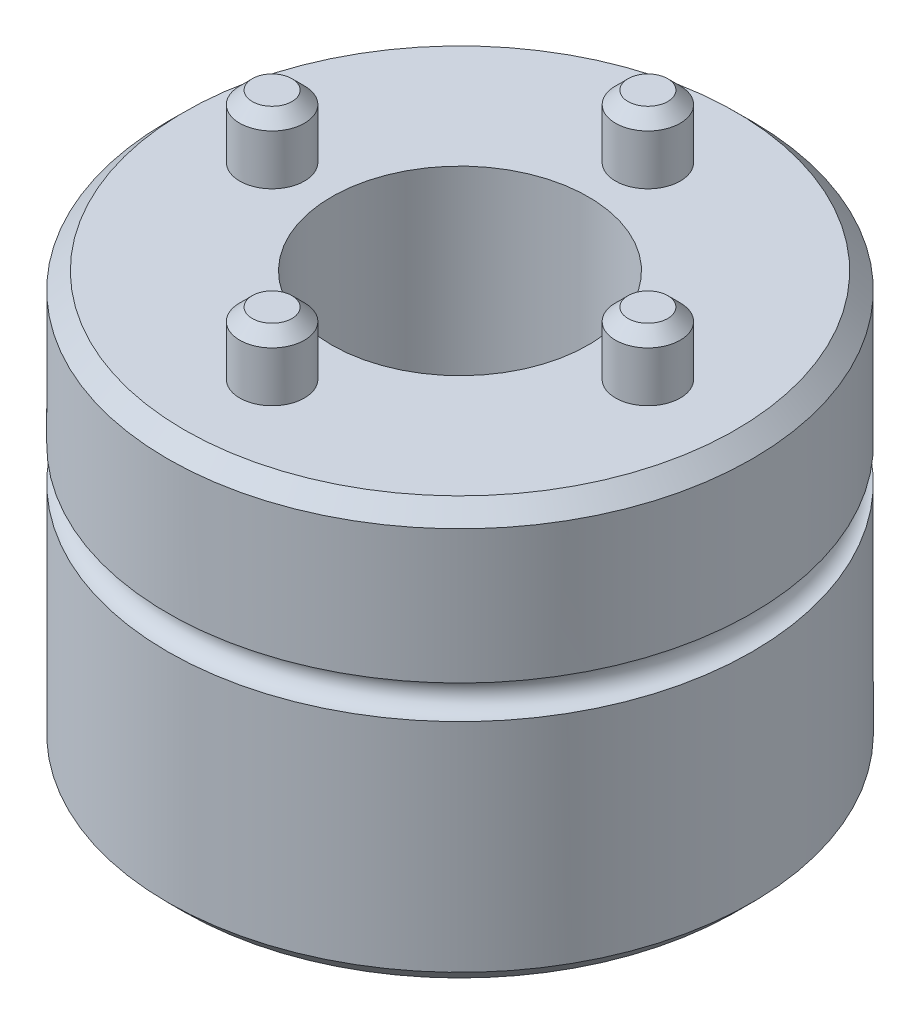
SolidWorks part; units mm, degrees
ref_plane "Front Plane" through (0, 0, 0) normal (0, 0, 1) x (1, 0, 0)
ref_plane "Top Plane" through (0, 0, 0) normal (0, 1, 0) x (1, 0, 0)
ref_plane "Right Plane" through (0, 0, 0) normal (1, 0, 0) x (0, 0, -1)
sketch "Sketch1" plane through (0, 0, 0) normal (0, 1, 0) x (1, 0, 0)
  circle A0 centre (0, 0) radius 7
  circle A1 centre (0, 0) radius 0.975
  dimension "D1" = 1.95
  dimension "D2" = 14
extrude "Boss-Extrude1" add sketch "Sketch1" along normal mid plane 10
sketch "Sketch3" plane through (0, 5, 0) normal (0, 1, 0) x (1, 0, 0)
  circle A0 centre (0, 0) radius 3.075
  dimension "D1" = 6.15
extrude "Cut-Extrude1" cut sketch "Sketch3" against normal blind 5
sketch "Sketch4" plane through (0, 5, 0) normal (0, -1, 0) x (1, 0, 0)
  circle A0 centre (4.5, 0) radius 0.775
  dimension "D1" = 1.55
  dimension "D2" = 4.5
extrude "Boss-Extrude3" add sketch "Sketch4" against normal blind 1.5
chamfer "Chamfer1" distance 0.3 angle 45 1 edges at (4.5, 6.5, -0.775)
pattern_circular "CirPattern1" count 4 over 360 about axis through (0, 0, 0) along (0, 1, 0) of "Boss-Extrude3", "Chamfer1"
sketch "Sketch8" plane through (0, 0, 0) normal (0, 0, 1) x (1, 0, 0)
  line L0 (0, 0) -> (0, 2) construction
  line L1 (7, 5) -> (-7, 5) construction
  line L2 (7, 5) -> (-7, 5) construction
  circle A0 centre (7, 1) radius 0.4
  point P5 (0, 1)
  dimension "D1" = 0.8
  dimension "D2" = 2
revolve "Cut-Revolve1" cut sketch "Sketch8" angle 360 about L0
chamfer "Chamfer2" distance 0.4 angle 45 2 edges at (0, -5, 7) (0, 5, 7)
